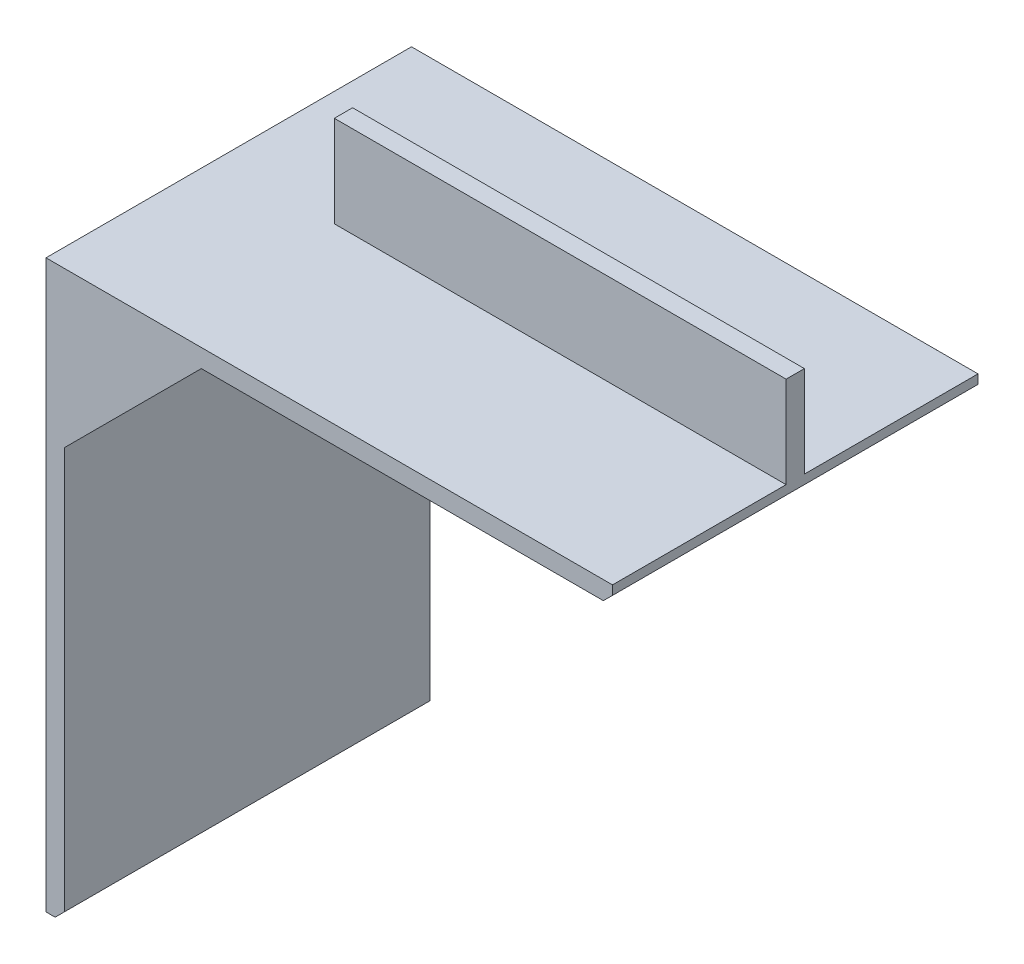
SolidWorks part; units mm, degrees
ref_plane "Front Plane" through (0, 0, 0) normal (0, 0, 1) x (1, 0, 0)
ref_plane "Top Plane" through (0, 0, 0) normal (0, 1, 0) x (1, 0, 0)
ref_plane "Right Plane" through (0, 0, 0) normal (1, 0, 0) x (0, 0, -1)
sketch "Sketch2" plane through (0, 0, 0) normal (0, 0, 1) x (1, 0, 0)
  line L0 (0, 0) -> (60, 0)
  line L1 (60, 0) -> (60, 2)
  line L2 (60, 2) -> (-2, 2)
  line L3 (-2, 2) -> (-2, -60)
  line L4 (-2, -60) -> (0, -60)
  line L5 (0, -60) -> (0, 0)
  dimension "D1" = 2
  dimension "D2" = 2
  dimension "D3" = 60
  dimension "D4" = 60
extrude "Boss-Extrude1" add sketch "Sketch2" along normal blind 40
sketch "Sketch3" plane through (0, 0, 40) normal (0, 0, 1) x (1, 0, 0)
  line L0 (15, 0) -> (0, 0)
  line L1 (0, 0) -> (60, 0) construction
  line L2 (0, 0) -> (0, -15)
  line L3 (0, -60) -> (0, 0) construction
  line L4 (0, -15) -> (15, 0)
  dimension "D1" = 15
  dimension "D2" = 15
extrude "Boss-Extrude2" add sketch "Sketch3" against normal blind 3
pattern_linear "LPattern1" count 2 spacing 37 along (0, 0, -1) of "Boss-Extrude2"
sketch "Sketch4" plane through (0, 0, 40) normal (0, 0, 1) x (1, 0, 0)
chamfer "Chamfer1" distance 1 angle 45 2 edges at (60, 0, 20) (0, -60, 20)
sketch "Sketch6" plane through (0, 0, 40) normal (0, 0, 1) x (1, 0, 0)
  line L0 (-2, 2) -> (7.5, -7.5) construction
  line L1 (0, -15) -> (15, 0) construction
  line L2 (-2, -10.5549) -> (-2, -60)
  line L3 (-2, 2) -> (-2, -60) construction
  line L4 (-2, -60) -> (-12, -60)
  line L5 (-12, -60) -> (-12, -10.5549)
  line L6 (-12, -10.5549) -> (-2, -10.5549)
  line L7 (10.5549, 12) -> (10.5549, 2)
  line L8 (60, 12) -> (10.5549, 12)
  line L9 (60, 2) -> (60, 12)
  line L10 (10.5549, 2) -> (60, 2)
  dimension "D1" = 10
extrude "Boss-Extrude5" add sketch "Sketch6" along normal blind 2 from offset 21 offset against normal yes
